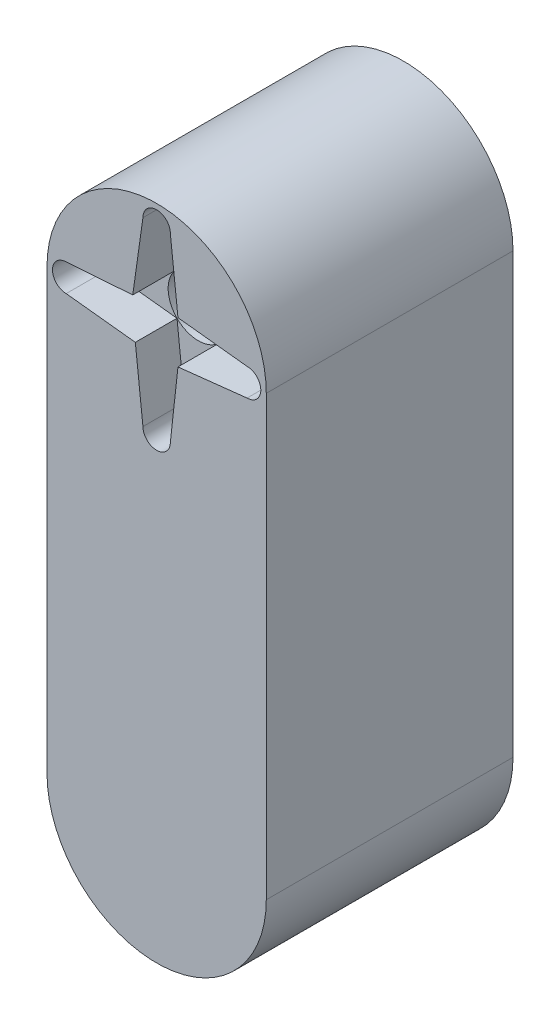
SolidWorks part; units mm, degrees
ref_plane "Alzado" through (0, 0, 0) normal (1, 0, 0) x (0, 1, 0)
ref_plane "Planta" through (0, 0, 0) normal (0, 0, 1) x (0, 1, 0)
ref_plane "Vista lateral" through (0, 0, 0) normal (0, 1, 0) x (-1, 0, 0)
sketch "Croquis1" plane through (0, 0, 0) normal (0, 0, 1) x (0, 1, 0)
  circle A2 centre (-40, 0) radius 20
  circle A3 centre (40, 0) radius 20
extrude "Saliente-Extruir1" add sketch "Croquis1" along normal blind 45
sketch "Croquis2" plane through (0, 0, 45) normal (0, 0, 1) x (1, 0, 0)
  line L0 (-20, -40) -> (-20, 40)
  line L1 (-20, 40) -> (20, 40)
  line L2 (20, 40) -> (20, -40)
  line L3 (20, -40) -> (-20, -40)
  circle A0 centre (0, -40) radius 20 construction
  circle A1 centre (0, 40) radius 20 construction
extrude "Saliente-Extruir2" add sketch "Croquis2" against normal blind 45
sketch "Croquis3" plane through (0, 0, 45) normal (0, 0, 1) x (1, 0, 0)
  line L18 (-16.5, 42.5) -> (-4.356, 43.3579)
  line L19 (-2.5, 56.5) -> (-4.356, 43.3579)
  line L20 (2.5, 56.5) -> (3.8891, 43.8891)
  line L21 (3.8891, 43.8891) -> (16.5, 42.5)
  line L22 (3.8891, 36.1109) -> (16.5, 37.5)
  line L23 (3.8891, 36.1109) -> (2.5, 23.5)
  line L24 (-2.5, 23.5) -> (-3.8891, 36.1109)
  line L25 (-16.5, 37.5) -> (-3.8891, 36.1109)
  arc A0 (-16.5, 42.5) -> (-16.5, 37.5) centre (-16.5, 40) ccw
  arc A1 (2.5, 56.5) -> (-2.5, 56.5) centre (0, 56.5) ccw
  arc A2 (-2.5, 23.5) -> (2.5, 23.5) centre (0, 23.5) ccw
  arc A3 (16.5, 37.5) -> (16.5, 42.5) centre (16.5, 40) ccw
extrude "Cortar-Extruir2" cut sketch "Croquis3" against normal blind 7.6
sketch "Croquis4" plane through (0, 0, 45) normal (0, 0, 1) x (1, 0, 0)
  circle A0 centre (0, 40) radius 5.5
extrude "Cortar-Extruir3" cut sketch "Croquis4" against normal blind 50
sketch "Croquis5" plane through (0, 0, 0) normal (0, 0, -1) x (1, 0, 0)
  line L0 (10, 50) -> (-10, 50)
  line L4 (-10, 50) -> (-10, 10)
  line L5 (-10, 10) -> (10, 10)
  line L6 (10, 10) -> (10, 50)
extrude "Cortar-Extruir4" cut sketch "Croquis5" against normal blind 40
sketch "Croquis6" plane through (0, 0, 0) normal (0, 0, -1) x (1, 0, 0)
  line L1 (-10, 50) -> (10, 50)
  line L2 (-10, 50) -> (-10, 56.5)
  line L3 (-10, 56.5) -> (10, 56.5)
  line L4 (10, 50) -> (10, 56.5)
  line L5 (10, 10) -> (-10, 10)
  line L6 (10, 10) -> (10, 3)
  line L7 (10, 3) -> (-10, 3)
  line L8 (-10, 10) -> (-10, 3)
  dimension "D1" = 7
extrude "Cortar-Extruir5" cut sketch "Croquis6" against normal blind 12
sketch "Croquis7" plane through (0, 0, 0) normal (0, 0, -1) x (1, 0, 0)
  line L1 (-10, 50) -> (10, 50)
  line L2 (-10, 50) -> (-10, 63.9109)
  line L3 (-10, 63.9109) -> (10, 63.9109)
  line L4 (10, 50) -> (10, 63.9109)
extrude "Cortar-Extruir6" cut sketch "Croquis7" against normal blind 12 from offset 27
